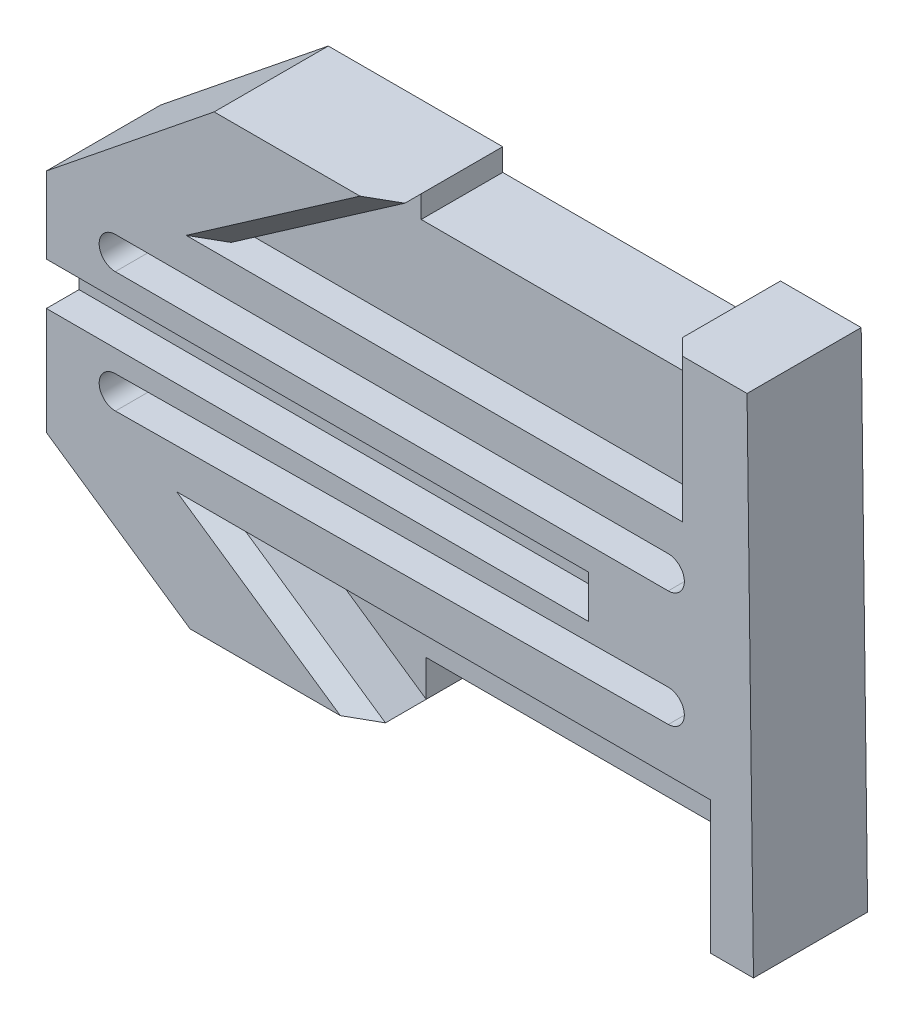
SolidWorks part; units mm, degrees
ref_plane "Front Plane" through (0, 0, 0) normal (0, 0, 1) x (1, 0, 0)
ref_plane "Top Plane" through (0, 0, 0) normal (0, 1, 0) x (1, 0, 0)
ref_plane "Right Plane" through (0, 0, 0) normal (1, 0, 0) x (0, 0, -1)
sketch "Sketch1" plane through (0, 0, 0) normal (0, 0, 1) x (1, 0, 0)
  line L0 (219.3827, 187.2724) -> (219.3827, 231.3787)
  line L1 (219.3827, 231.3787) -> (252.0475, 257.6683)
  line L2 (252.0475, 257.6683) -> (286.0113, 257.6683)
  line L3 (340.0957, 257.6683) -> (340.0957, 262.0711)
  line L4 (340.0957, 262.0711) -> (355.81, 262.0711)
  line L5 (355.81, 262.0711) -> (357.0595, 164.1292)
  line L6 (357.0595, 163.2618) -> (357.0595, 173.035) construction
  line L7 (357.0595, 164.1292) -> (345.4716, 164.1292)
  line L8 (345.4716, 164.1292) -> (345.4716, 189.979)
  line L9 (345.4716, 189.979) -> (250.3781, 189.979)
  line L10 (250.3781, 189.979) -> (282.2301, 168.1484)
  line L11 (282.2301, 168.1484) -> (247.351, 168.1484)
  line L12 (247.351, 168.1484) -> (219.3827, 187.2724)
  line L15 (286.0113, 257.6683) -> (286.0113, 253.3355)
  line L16 (286.0113, 253.3355) -> (340.0957, 253.3355)
  line L17 (340.0957, 257.6683) -> (340.0957, 253.3355)
extrude "Boss-Extrude1" add sketch "Sketch1" along normal blind 22.225 contours L2 L15 L16 L17 L3 L4 L5 L7 L8 L9 L10 L11 L12 L0 L1
sketch "Sketch2" plane through (0, 0, 0) normal (0, 0, 1) x (1, 0, 0)
  line L0 (345.4716, 164.1292) -> (345.4716, 189.979) construction
  line L1 (345.4716, 175.2029) -> (250.3781, 175.2029)
  line L2 (345.4716, 175.2029) -> (345.4716, 189.979)
  line L3 (345.4716, 189.979) -> (250.3781, 189.979)
  line L4 (250.3781, 175.2029) -> (250.3781, 189.979)
extrude "Boss-Extrude2" add sketch "Sketch2" along normal blind 11.1125
sketch "Sketch3" plane through (0, 0, 22.225) normal (0, 0, 1) x (1, 0, 0)
  line L0 (219.3827, 187.2724) -> (219.3827, 231.3787) construction
  line L1 (219.3827, 216.5112) -> (324.9159, 216.5112)
  line L2 (219.3827, 216.5112) -> (219.3827, 208.1924)
  line L3 (219.3827, 208.1924) -> (324.9159, 208.1924)
  line L4 (324.9159, 216.5112) -> (324.9159, 208.1924)
  line L5 (340.0957, 253.3355) -> (340.0957, 234.1275)
  line L6 (340.0957, 234.1275) -> (252.167, 234.1275)
  line L7 (252.167, 234.1275) -> (286.0113, 257.6683)
  line L8 (286.0113, 257.6683) -> (340.0957, 253.3355)
extrude "Cut-Extrude1" cut sketch "Sketch3" against normal blind 6.35
sketch "Sketch4" plane through (0, 0, 22.225) normal (0, 0, 1) x (1, 0, 0)
  line L0 (232.7998, 224.2485) -> (340.4595, 224.2485) construction
  line L1 (232.7998, 227.3891) -> (340.4595, 227.3891)
  line L2 (232.7998, 221.108) -> (340.4595, 221.108)
  line L3 (232.7998, 200.7601) -> (340.4551, 201.7388) construction
  line L4 (232.7712, 203.9005) -> (340.4265, 204.8792)
  line L5 (232.8283, 197.6197) -> (340.4836, 198.5984)
  arc A0 (232.7998, 227.3891) -> (232.7998, 221.108) centre (232.7998, 224.2485) ccw
  arc A1 (340.4595, 221.108) -> (340.4595, 227.3891) centre (340.4595, 224.2485) ccw
  arc A2 (232.7712, 203.9005) -> (232.8283, 197.6197) centre (232.7998, 200.7601) ccw
  arc A3 (340.4836, 198.5984) -> (340.4265, 204.8792) centre (340.4551, 201.7388) ccw
  point P2 (286.6297, 224.2485)
  point P7 (286.6274, 201.2494)
extrude "Cut-Extrude2" cut sketch "Sketch4" against normal through all
sketch "Sketch5" plane through (0, 0, 11.1125) normal (0, 0, 1) x (1, 0, 0)
  line L0 (282.2301, 168.1484) -> (282.2301, 175.2029)
  line L1 (271.9373, 175.2029) -> (345.4716, 175.2029) construction
  line L2 (282.2301, 175.2029) -> (271.9373, 175.2029)
  line L3 (271.9373, 175.2029) -> (282.2301, 168.1484)
extrude "Boss-Extrude3" add sketch "Sketch5" against normal up to surface (11.1125 mm away) up to face at (286.6274, 201.2494, 0)
chamfer "Chamfer1" distance 3.175 angle 45 4 edges at (266.3041, 179.0637, 22.225) (269.0892, 245.8979, 22.225) (345.4716, 177.0541, 22.225) (340.0957, 248.0993, 22.225)
